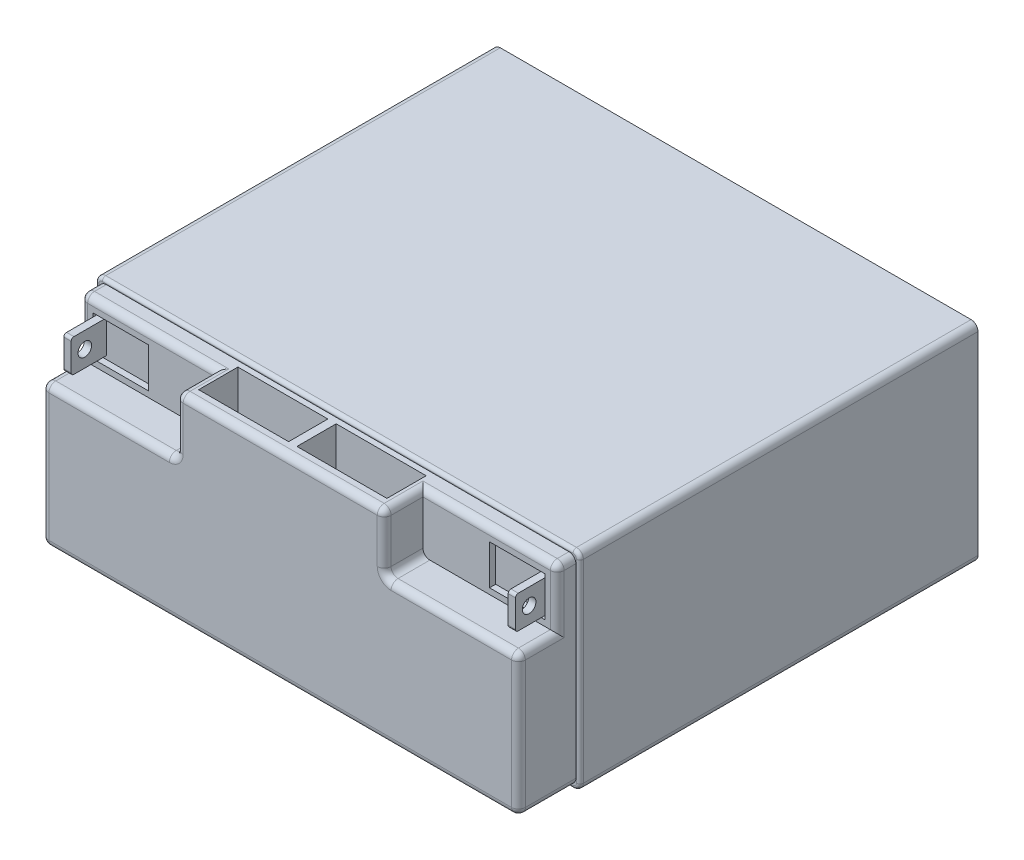
SolidWorks part; units mm, degrees
ref_plane "前基準面" through (0, 0, 0) normal (0, 0, 1) x (1, 0, 0)
ref_plane "上基準面" through (0, 0, 0) normal (0, 1, 0) x (1, 0, 0)
ref_plane "右基準面" through (0, 0, 0) normal (1, 0, 0) x (0, 0, -1)
ref_plane "平面4" through (0, -62.2132, 0) normal (0, -1, 0) x (1, 0, 0)
sketch "草圖1" plane through (0, -62.2132, 0) normal (0, -1, 0) x (1, 0, 0)
  line L0 (144.6869, 146.05) -> (-33.1131, 146.05)
  line L1 (-33.1131, 146.05) -> (-33.1131, 0)
  line L2 (-33.1131, 0) -> (144.6869, 0)
  line L3 (144.6869, 0) -> (144.6869, 146.05)
extrude "填料-伸長1" add sketch "草圖1" against normal blind 76.2
sketch "草圖2" plane through (0, 0, 146.05) normal (0, 0, 1) x (1, 0, 0)
  line L0 (143.2096, -60.7358) -> (-31.6357, -60.7358)
  line L1 (-31.6357, -60.7358) -> (-31.6357, 12.5094)
  line L2 (-31.6357, 12.5094) -> (143.2096, 12.5094)
  line L3 (143.2096, 12.5094) -> (143.2096, -60.7358)
extrude "填料-伸長2" add sketch "草圖2" along normal blind 21.082
sketch "草圖3" plane through (0, 12.5094, 0) normal (0, 1, 0) x (-1, 0, 0)
  line L0 (31.6357, 167.132) -> (-17.6403, 167.132)
  line L1 (-17.6403, 167.132) -> (-17.6403, 152.908)
  line L2 (-17.6403, 152.908) -> (31.6357, 152.908)
  line L3 (31.6357, 152.908) -> (31.6357, 167.132)
extrude "除料-伸長1" cut sketch "草圖3" against normal blind 21.336
sketch "草圖4" plane through (0, 0, 152.908) normal (0, 0, 1) x (1, 0, 0)
  line L0 (-27.0726, 6.6326) -> (-24.3791, 6.6326)
  line L1 (-24.3791, 6.6326) -> (-24.3791, -5.3674)
  line L2 (-24.3791, -5.3674) -> (-27.0726, -5.3674)
  line L3 (-27.0726, -5.3674) -> (-27.0726, 6.6326)
extrude "填料-伸長3" add sketch "草圖4" along normal blind 10.746
sketch "草圖5" plane through (0, 0, 152.908) normal (0, 0, 1) x (1, 0, 0)
  line L0 (-6.7872, -6.6776) -> (-6.7872, 7.9428)
  line L1 (-6.7872, 7.9428) -> (-27.0726, 7.9428)
  line L2 (-27.0726, 7.9428) -> (-27.0726, 6.6326)
  line L3 (-27.0726, 6.6326) -> (-24.3791, 6.6326)
  line L4 (-24.3791, 6.6326) -> (-24.3791, -5.3674)
  line L5 (-24.3791, -5.3674) -> (-27.0726, -5.3674)
  line L6 (-27.0726, -5.3674) -> (-27.0726, -6.6776)
  line L7 (-27.0726, -6.6776) -> (-6.7872, -6.6776)
extrude "除料-伸長2" cut sketch "草圖5" against normal blind 2.254
sketch "草圖6" plane through (0, 0, 167.132) normal (0, 0, 1) x (1, 0, 0)
  line L0 (93.9336, 12.5094) -> (93.9336, -8.8266)
  line L1 (93.9336, -8.8266) -> (143.2096, -8.8266)
  line L2 (143.2096, -8.8266) -> (143.2096, 12.5094)
  line L3 (143.2096, 12.5094) -> (93.9336, 12.5094)
extrude "除料-伸長3" cut sketch "草圖6" against normal blind 14.224
sketch "草圖7" plane through (0, 0, 152.908) normal (0, 0, 1) x (1, 0, 0)
  line L0 (138.6465, -5.3674) -> (135.9529, -5.3674)
  line L1 (135.9529, -5.3674) -> (135.9529, 6.6326)
  line L2 (135.9529, 6.6326) -> (138.6465, 6.6326)
  line L3 (138.6465, 6.6326) -> (138.6465, -5.3674)
extrude "填料-伸長4" add sketch "草圖7" along normal blind 10.746
sketch "草圖8" plane through (0, 0, 152.908) normal (0, 0, 1) x (1, 0, 0)
  line L0 (118.361, 7.9428) -> (118.361, -6.6776)
  line L1 (118.361, -6.6776) -> (138.6465, -6.6776)
  line L2 (138.6465, -6.6776) -> (138.6465, -5.3674)
  line L3 (138.6465, -5.3674) -> (135.9529, -5.3674)
  line L4 (135.9529, -5.3674) -> (135.9529, 6.6326)
  line L5 (135.9529, 6.6326) -> (138.6465, 6.6326)
  line L6 (138.6465, 6.6326) -> (138.6465, 7.9428)
  line L7 (138.6465, 7.9428) -> (118.361, 7.9428)
extrude "除料-伸長4" cut sketch "草圖8" against normal blind 2.254
sketch "草圖9" plane through (0, 12.5094, 0) normal (0, 1, 0) x (-1, 0, 0)
  line L0 (-54.2629, 148.1138) -> (-21.2429, 148.1138)
  line L1 (-21.2429, 148.1138) -> (-21.2429, 162.5135)
  line L2 (-21.2429, 162.5135) -> (-54.2629, 162.5135)
  line L3 (-54.2629, 162.5135) -> (-54.2629, 148.1138)
extrude "除料-伸長5" cut sketch "草圖9" against normal blind 19.05
sketch "草圖10" plane through (0, 12.5094, 0) normal (0, 1, 0) x (-1, 0, 0)
  line L0 (-90.3309, 148.1138) -> (-57.3109, 148.1138)
  line L1 (-57.3109, 148.1138) -> (-57.3109, 162.5135)
  line L2 (-57.3109, 162.5135) -> (-90.3309, 162.5135)
  line L3 (-90.3309, 162.5135) -> (-90.3309, 148.1138)
extrude "除料-伸長6" cut sketch "草圖10" against normal blind 19.05
sketch "草圖11" plane through (0, -60.7358, 0) normal (0, -1, 0) x (1, 0, 0)
  line L0 (-8.7757, 162.8434) -> (-8.7757, 147.6421)
  line L1 (-8.7757, 147.6421) -> (54.7243, 147.6421)
  line L2 (54.7243, 147.6421) -> (54.7243, 162.8434)
  line L3 (54.7243, 162.8434) -> (-8.7757, 162.8434)
extrude "除料-伸長7" cut sketch "草圖11" against normal blind 19.558
sketch "草圖12" plane through (0, -60.7358, 0) normal (0, -1, 0) x (1, 0, 0)
  line L0 (56.8496, 162.8434) -> (56.8496, 147.6421)
  line L1 (56.8496, 147.6421) -> (120.3496, 147.6421)
  line L2 (120.3496, 147.6421) -> (120.3496, 162.8434)
  line L3 (120.3496, 162.8434) -> (56.8496, 162.8434)
extrude "除料-伸長8" cut sketch "草圖12" against normal blind 19.558
hole_wizard "#10 餘隙孔1" positions "草圖14" profile "草圖13" hole size "#10" standard "Ansi Inch"
sketch "草圖14" plane through (-24.3791, 0, 0) normal (1, 0, 0) x (0, 0, -1)
  point P0 (-158.654, 0.6326)
sketch "草圖13" plane through (-24.3791, 0.6326, 158.654) normal (0, 1, 0) x (0, 0, -1)
  line L0 (0, 0) -> (0, 8.734)
  line L1 (0, 8.734) -> (2.5, 8.734)
  line L2 (2.5, 8.734) -> (2.5, 0)
  line L5 (2.5, 0) -> (0, 0)
  line L11 (0, -6.35) -> (0, 107.95) construction
  dimension "貫穿孔直徑" = 5
  dimension "貫穿孔深度" = 8.734
hole_wizard "#10 餘隙孔2" positions "草圖16" profile "草圖15" hole size "#10" standard "Ansi Inch"
sketch "草圖16" plane through (135.9529, 0, 0) normal (-1, 0, 0) x (0, 0, 1)
  point P0 (158.654, 0.6326)
sketch "草圖15" plane through (135.9529, 0.6326, 158.654) normal (0, 1, 0) x (0, 0, 1)
  line L0 (0, 0) -> (0, 8.734)
  line L1 (0, 8.734) -> (2.5, 8.734)
  line L2 (2.5, 8.734) -> (2.5, 0)
  line L5 (2.5, 0) -> (0, 0)
  line L11 (0, -6.35) -> (0, 107.95) construction
  dimension "貫穿孔直徑" = 5
  dimension "貫穿孔深度" = 8.734
fillet "圓角1" radius 2.54 26 edges at (-31.6357, 1.8414, 152.908) (-31.6357, 12.5094, 149.479) (-31.6357, -8.8266, 160.02) (-6.9977, 12.5094, 152.908) (-31.6357, -60.7358, 156.591) (-31.6357, -34.7812, 167.132) (17.6403, 1.8414, 167.132) (-6.9977, -8.8266, 167.132) (17.6403, 12.5094, 160.02) (143.2096, 12.5094, 149.479) (118.5716, 12.5094, 152.908) (143.2096, -60.7358, 156.591) (55.7869, -60.7358, 167.132) (93.9336, 12.5094, 160.02) (55.7869, 12.5094, 167.132) (143.2096, 1.8414, 152.908) (143.2096, -34.7812, 167.132) (143.2096, -8.8266, 160.02) (118.5716, -8.8266, 167.132) (93.9336, -8.8266, 160.02) (93.9336, 1.8414, 167.132) (-33.1131, 13.9868, 73.025) (17.6403, -8.8266, 160.02) (-33.1131, -62.2132, 73.025) (144.6869, -62.2132, 73.025) (144.6869, 13.9868, 73.025)
fillet "圓角2" radius 1 4 edges at (-25.7258, -5.3674, 163.654) (137.2997, -5.3674, 163.654) (-25.7258, 6.6326, 163.654) (137.2997, 6.6326, 163.654)
fillet "圓角3" radius 1.27 8 edges at (-33.1131, -24.1132, 146.05) (-32.3691, -61.4693, 146.05) (-32.3691, 13.2428, 146.05) (55.7869, -62.2132, 146.05) (55.7869, 13.9868, 146.05) (143.943, -61.4693, 146.05) (143.943, 13.2428, 146.05) (144.6869, -24.1132, 146.05)
